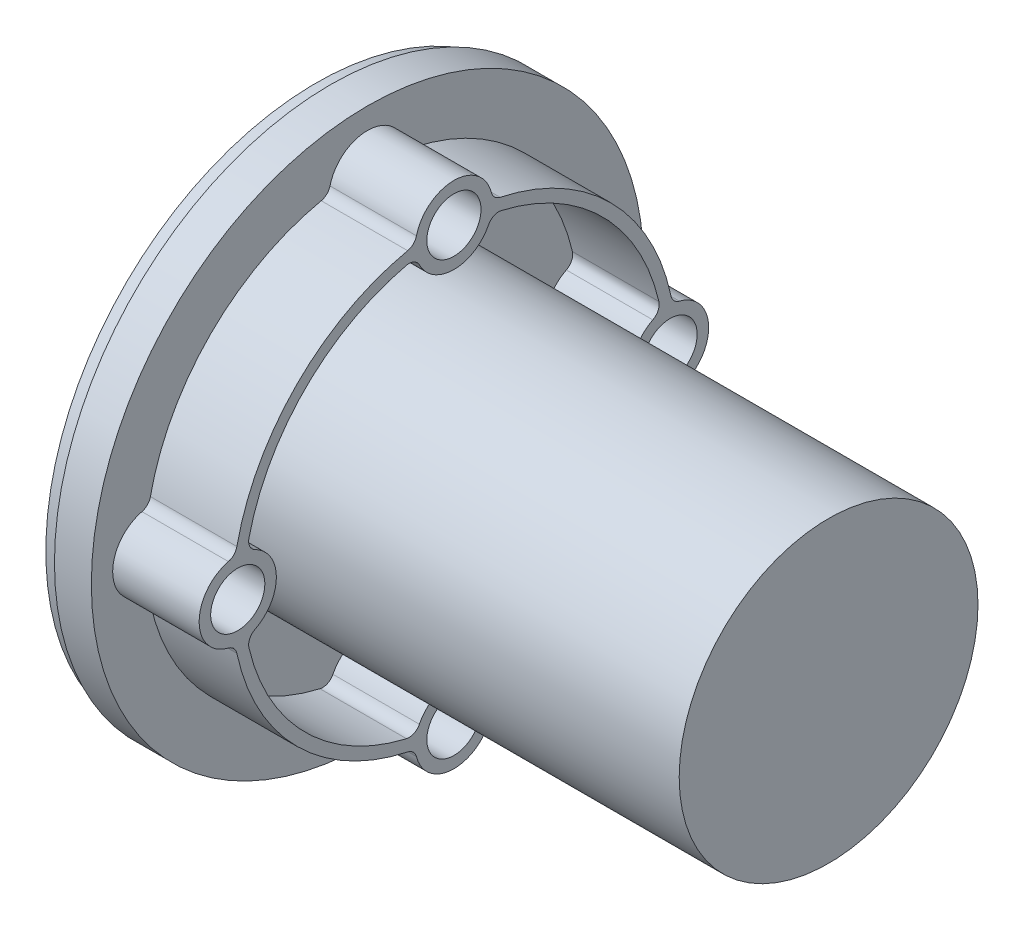
SolidWorks part; units mm, degrees
ref_plane "Front Plane" through (0, 0, 0) normal (0, 0, 1) x (1, 0, 0)
ref_plane "Top Plane" through (0, 0, 0) normal (0, 1, 0) x (1, 0, 0)
ref_plane "Right Plane" through (0, 0, 0) normal (1, 0, 0) x (0, 0, -1)
sketch "Sketch1" plane through (0, 0, 0) normal (1, 0, 0) x (0, 0, -1)
  circle A0 centre (0, 0) radius 25.0825
  dimension "D1" = 50.165
extrude "Extrude-Thin1" add sketch "Sketch1" along normal blind 21.59 thin
sketch "Sketch2" plane through (21.59, 0, 0) normal (1, 0, 0) x (0, 0, -1)
  circle A0 centre (0, 0) radius 59.563
  dimension "D1" = 119.126
extrude "Boss-Extrude1" add sketch "Sketch2" against normal blind 3.175 separate body
sketch "Sketch3" plane through (18.415, 0, 0) normal (-1, 0, 0) x (0, 0, 1)
  line L0 (35.687, 0) -> (47.625, 0) construction
  line L1 (35.687, 5.969) -> (47.625, 5.969)
  line L2 (35.687, -5.969) -> (47.625, -5.969)
  line L3 (-5.969, -35.687) -> (-5.969, -47.625)
  line L4 (5.969, -35.687) -> (5.969, -47.625)
  line L5 (0, -35.687) -> (0, -47.625) construction
  line L6 (-35.687, 5.969) -> (-47.625, 5.969)
  line L7 (-35.687, -5.969) -> (-47.625, -5.969)
  line L8 (-35.687, 0) -> (-47.625, 0) construction
  line L9 (5.969, 35.687) -> (5.969, 47.625)
  line L10 (-5.969, 35.687) -> (-5.969, 47.625)
  line L11 (0, 35.687) -> (0, 47.625) construction
  arc A0 (35.687, 5.969) -> (35.687, -5.969) centre (35.687, 0) ccw
  arc A1 (47.625, -5.969) -> (47.625, 5.969) centre (47.625, 0) ccw
  arc A2 (5.969, -35.687) -> (-5.969, -35.687) centre (0, -35.687) ccw
  arc A3 (-5.969, -47.625) -> (5.969, -47.625) centre (0, -47.625) ccw
  arc A4 (-35.687, -5.969) -> (-35.687, 5.969) centre (-35.687, 0) ccw
  arc A5 (-47.625, 5.969) -> (-47.625, -5.969) centre (-47.625, 0) ccw
  arc A6 (-5.969, 35.687) -> (5.969, 35.687) centre (0, 35.687) ccw
  arc A7 (5.969, 47.625) -> (-5.969, 47.625) centre (0, 47.625) ccw
  point P3 (41.656, 0)
  point P13 (0, -41.656)
  point P20 (-41.656, 0)
  point P27 (0, 41.656)
  point P32 (0, 0)
  dimension "D2" = 5.969
  dimension "D1" = 47.625
  dimension "D3" = 11.938
  dimension "D4" = 4
extrude "Cut-Extrude1" cut sketch "Sketch3" against normal through all
sketch "Sketch4" plane through (21.59, 0, 0) normal (1, 0, 0) x (0, 0, -1)
  circle A0 centre (0, 0) radius 60.833
  dimension "D1" = 121.666
extrude "Boss-Extrude2" add sketch "Sketch4" along normal blind 8.128 separate body
sketch "Sketch5" plane through (18.415, 0, 0) normal (-1, 0, 0) x (0, 0, 1)
  circle A0 centre (0, 0) radius 25.0825 construction
  circle A1 centre (0, 0) radius 25.0825
  arc A2 (-5.969, -47.625) -> (5.969, -47.625) centre (0, -47.625) ccw construction
  arc A3 (47.625, -5.969) -> (47.625, 5.969) centre (47.625, 0) ccw construction
  arc A4 (-47.625, 5.969) -> (-47.625, -5.969) centre (-47.625, 0) ccw construction
  arc A5 (5.969, 47.625) -> (-5.969, 47.625) centre (0, 47.625) ccw construction
  arc A6 (-5.969, -47.625) -> (5.969, -47.625) centre (0, -47.625) ccw
  arc A7 (47.625, -5.969) -> (47.625, 5.969) centre (47.625, 0) ccw
  arc A8 (-47.625, 5.969) -> (-47.625, -5.969) centre (-47.625, 0) ccw
  arc A9 (5.969, 47.625) -> (-5.969, 47.625) centre (0, 47.625) ccw
  circle A10 centre (0, 47.625) radius 5.969
  circle A11 centre (47.625, 0) radius 5.969
  circle A12 centre (-47.625, 0) radius 5.969
  circle A13 centre (0, -47.625) radius 5.969
  arc M4 (47.625, 5.969) -> (47.625, -5.969) centre (47.625, 0) cw
  arc M8 (5.969, -47.625) -> (-5.969, -47.625) centre (0, -47.625) cw
  arc M12 (-47.625, -5.969) -> (-47.625, 5.969) centre (-47.625, 0) cw
  arc M16 (-5.969, 47.625) -> (5.969, 47.625) centre (0, 47.625) cw
extrude "Cut-Extrude2" cut sketch "Sketch5" against normal through all contours A12 M12 | A10 M16 | A11 M4 | A13 M8 | A1
sketch "Sketch6" plane through (29.718, 0, 0) normal (1, 0, 0) x (0, 0, -1)
  circle A0 centre (-47.625, 0) radius 5.969 construction
  circle A1 centre (-47.625, 0) radius 5.969
  circle A2 centre (-47.625, 0) radius 8.509
  arc A3 (-47.625, 0) -> (0, 47.625) centre (0, 0) cw construction
  arc A4 (-46.355, 0) -> (0, 46.355) centre (0, 0) cw
  arc A5 (-48.895, 0) -> (0, 48.895) centre (0, 0) cw
  arc A6 (0, 46.355) -> (46.355, 0) centre (0, 0) cw
  arc A7 (0, 48.895) -> (48.895, 0) centre (0, 0) cw
  circle A8 centre (0, 47.625) radius 8.509
  circle A9 centre (0, 47.625) radius 5.969
  arc A10 (46.355, 0) -> (0, -46.355) centre (0, 0) cw
  arc A11 (48.895, 0) -> (0, -48.895) centre (0, 0) cw
  circle A12 centre (47.625, 0) radius 8.509
  circle A13 centre (47.625, 0) radius 5.969
  arc A14 (0, -46.355) -> (-46.355, 0) centre (0, 0) cw
  arc A15 (0, -48.895) -> (-48.895, 0) centre (0, 0) cw
  circle A16 centre (0, -47.625) radius 8.509
  circle A17 centre (0, -47.625) radius 5.969
  point P41 (0, 0)
  circle M3 centre (0, 47.625) radius 5.969
  circle M4 centre (0, -47.625) radius 5.969
  circle M7 centre (-47.625, 0) radius 5.969
  circle M8 centre (47.625, 0) radius 5.969
  dimension "D1" = 2.54
  dimension "D2" = 1.27
  dimension "D3" = 2.54
  dimension "D4" = 4
extrude "Boss-Extrude4" add sketch "Sketch6" along normal blind 19.05 separate body contours A14 A2 A4 M7 | A2 A15 A5 M7 | A5 A1 A4 A2 | A8 A5 A2 A4 | A15 A2 A14 A1 | A16 A14 A2 A15 | A5 A8 A4 M3 | A7 A8 A5 M3 | A4 A8 A6 M3 | A6 A8 A7 M3 | A12 A7 A8 A6 | A7 A12 A6 M8 | A6 A12 A10 M8 | A11 A12 A7 M8 | A10 A12 A11 M8 | A16 A11 A12 A10 | A10 A16 A14 M4 | A14 A16 A15 M4 | A15 A16 A11 M4 | A11 A16 A10 M4
fillet "Fillet1" radius 2.54 16 edges at (39.243, -8.2674, 45.6118) (39.243, 8.2674, 45.6118) (39.243, -8.4927, 48.1518) (39.243, 8.4927, 48.1518) (39.243, -48.1518, 8.4927) (39.243, -48.1518, -8.4927) (39.243, -8.4927, -48.1518) (39.243, 8.2674, -45.6118) (39.243, 48.1518, -8.4927) (39.243, 48.1518, 8.4927) (39.243, -45.6118, -8.2674) (39.243, -45.6118, 8.2674) (39.243, -8.2674, -45.6118) (39.243, 8.4927, -48.1518) (39.243, 45.6118, 8.2674) (39.243, 45.6118, -8.2674)
sketch "Sketch7" plane through (29.718, 0, 0) normal (1, 0, 0) x (0, 0, -1)
  circle A0 centre (0, 0) radius 32.9184
  dimension "D1" = 65.8368
extrude "Boss-Extrude5" add sketch "Sketch7" along normal blind 101.6
sketch "Sketch8" plane through (29.718, 0, 0) normal (-1, 0, 0) x (0, 0, 1)
  circle A0 centre (0, 0) radius 10.795
  dimension "D1" = 21.59
extrude "Boss-Extrude6" add sketch "Sketch8" along normal up to surface (29.718 mm away) up to face at (0, 0, -28.8925)
chamfer "Chamfer1" distance 1.27 angle 45 2 edges at (0, 0, -10.795) (0, 0, -28.8925)
